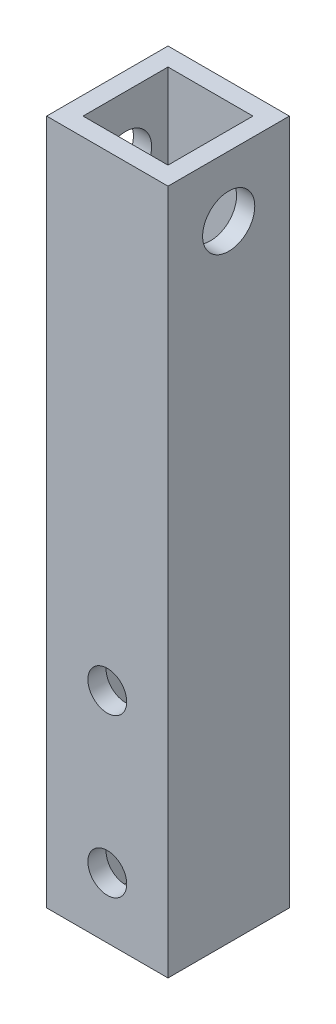
SolidWorks part; units mm, degrees
material "5052-H34"
ref_plane "正面" through (0, 0, 0) normal (0, 0, 1) x (1, 0, 0)
ref_plane "平面" through (0, 0, 0) normal (0, 1, 0) x (1, 0, 0)
ref_plane "右側面" through (0, 0, 0) normal (1, 0, 0) x (0, 0, -1)
sketch "ｽｹｯﾁ1" plane through (0, 0, 0) normal (0, 1, 0) x (1, 0, 0)
  line L1 (-5, 5) -> (5, 5)
  line L2 (-5, 5) -> (-5, -5)
  line L3 (-5, -5) -> (5, -5)
  line L4 (5, 5) -> (5, -5)
  line L5 (-5, 5) -> (5, -5) construction
  line L6 (-5, -5) -> (5, 5) construction
  point P0 (0, 0)
  dimension "D1" = 10
  dimension "D2" = 10
extrude "押し出し-薄板1" add sketch "ｽｹｯﾁ1" along normal blind 56.5 thin
sketch "ｽｹｯﾁ2" plane through (0, 0, 5) normal (0, 0, 1) x (1, 0, 0)
  line L0 (0, 0) -> (0, 18) construction
  circle A0 centre (0, 18) radius 1.6
  circle A1 centre (0, 5) radius 1.6
  dimension "D1" = 3.2
  dimension "D2" = 5
  dimension "D3" = 13
extrude "ｶｯﾄ - 押し出し1" cut sketch "ｽｹｯﾁ2" against normal through all
sketch "ｽｹｯﾁ3" plane through (5, 0, 0) normal (1, 0, 0) x (0, 0, -1)
  line L0 (0, 56.5) -> (0, 51.5) construction
  line L1 (-5, 56.5) -> (5, 56.5) construction
  circle A0 centre (0, 51.5) radius 2.15
  dimension "D2" = 4.3
  dimension "D1" = 5
extrude "ｶｯﾄ - 押し出し2" cut sketch "ｽｹｯﾁ3" against normal through all
